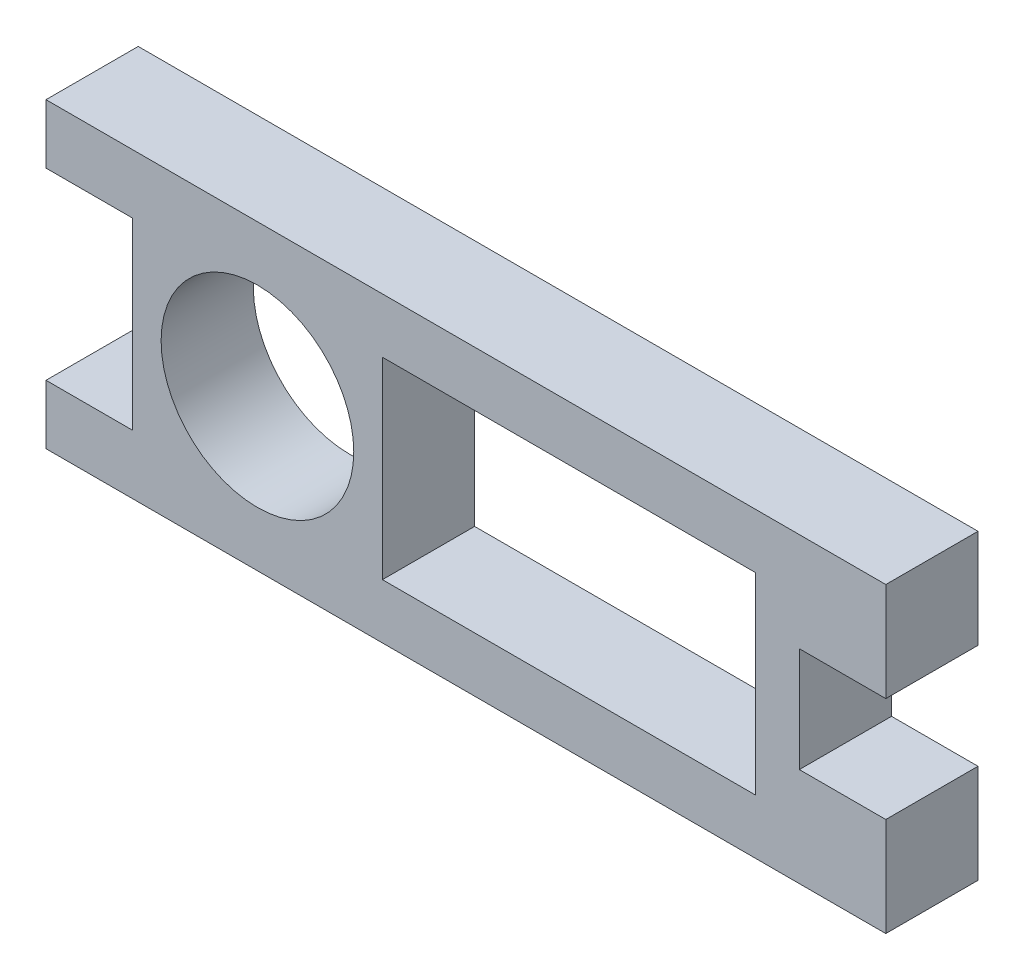
SolidWorks part; units mm, degrees
material "Acrylic (Medium-high impact)"
ref_plane "Front Plane" through (0, 0, 0) normal (0, 0, 1) x (1, 0, 0)
ref_plane "Top Plane" through (0, 0, 0) normal (0, 1, 0) x (1, 0, 0)
ref_plane "Right Plane" through (0, 0, 0) normal (1, 0, 0) x (0, 0, -1)
sketch "Sketch1" plane through (0, 0, 0) normal (0, 0, 1) x (1, 0, 0)
  line L0 (-297.9597, 397.165) -> (49702.0403, 397.165) construction
  line L1 (702.2903, 402.744) -> (702.2903, 391.586)
  line L2 (702.2903, 402.744) -> (697.0403, 402.744)
  line L3 (697.0403, 402.744) -> (697.0403, 406.344)
  line L4 (697.0403, 406.344) -> (748.0403, 406.344)
  line L5 (748.0403, 406.344) -> (748.0403, 400.344)
  line L6 (748.0403, 400.344) -> (742.7903, 400.344)
  line L7 (742.7903, 400.344) -> (742.7903, 393.986)
  line L8 (742.7903, 393.986) -> (748.0403, 393.986)
  line L9 (748.0403, 393.986) -> (748.0403, 387.986)
  line L10 (748.0403, 387.986) -> (697.0403, 387.986)
  line L11 (697.0403, 387.986) -> (697.0403, 391.586)
  line L12 (697.0403, 391.586) -> (702.2903, 391.586)
  line L13 (709.8808, -602.835) -> (709.8808, 49397.165) construction
  line L14 (717.4713, 391.315) -> (740.1403, 391.315)
  line L15 (717.4713, 391.315) -> (717.4713, 403.015)
  line L16 (717.4713, 403.015) -> (740.1403, 403.015)
  line L17 (740.1403, 391.315) -> (740.1403, 403.015)
  circle A0 centre (709.8808, 397.165) radius 5.85
  point P0 (702.2903, 397.165)
  point P19 (717.4713, 397.165)
  dimension "D10" = 11.7
  dimension "D1" = 11.158
  dimension "D2" = 3.6
  dimension "D3" = 40.5
  dimension "D4" = 5.25
  dimension "D5" = 5.25
  dimension "D6" = 6
  dimension "D7" = 22.669
  dimension "D8" = 2.65
  dimension "D9" = 11.7
extrude "Boss-Extrude1" add sketch "Sketch1" along normal blind 5.6
